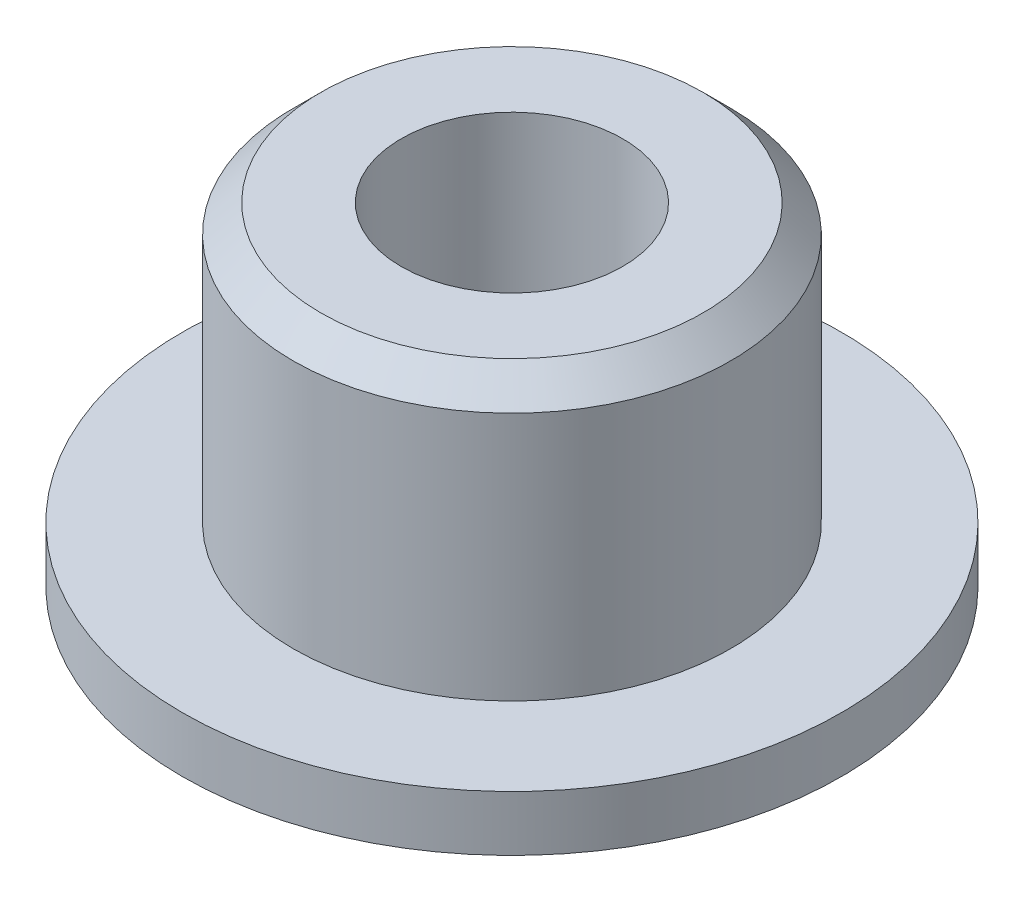
SolidWorks part; units mm, degrees
ref_plane "Ebene vorne" through (0, 0, 0) normal (0, 0, 1) x (1, 0, 0)
ref_plane "Ebene oben" through (0, 0, 0) normal (0, 1, 0) x (1, 0, 0)
ref_plane "Ebene rechts" through (0, 0, 0) normal (1, 0, 0) x (0, 0, -1)
sketch "Skizze1" plane through (0, 0, 0) normal (0, 0, 1) x (1, 0, 0)
  line L0 (0, 16.5599) -> (0, -21.0654) construction
  line L1 (2, 0) -> (2, -6)
  line L2 (3.95, 0) -> (3.95, -5)
  line L3 (3.95, -5) -> (5.95, -5)
  line L4 (5.95, -5) -> (5.95, -6)
  line L5 (5.95, -6) -> (2, -6)
  line L6 (3.95, 0) -> (2, 0)
  line L7 (-9.0777, 0) -> (11.1204, 0) construction
  point P7 (2.975, 0)
  dimension "D1" = 3.95
  dimension "D2" = 2
  dimension "D3" = 6
  dimension "D4" = 2
  dimension "D5" = 1
revolve "Rotation1" add sketch "Skizze1" angle 360 about L0
chamfer "Fase1" distance 0.5 angle 45 1 edges at (0, 0, 3.95)
chamfer "Fase2" distance 0.5 angle 45 1 edges at (0, -6, 2)
